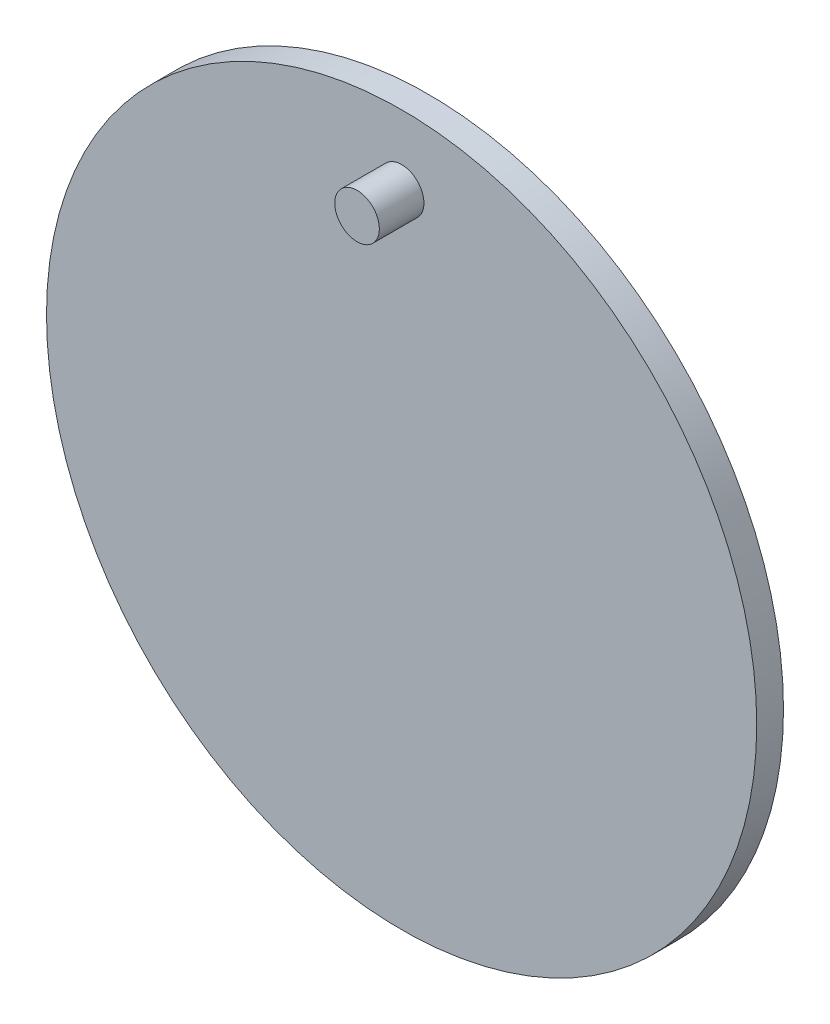
SolidWorks part; units mm, degrees
ref_plane "前视基准面" through (0, 0, 0) normal (0, 0, 1) x (1, 0, 0)
ref_plane "上视基准面" through (0, 0, 0) normal (0, 1, 0) x (1, 0, 0)
ref_plane "右视基准面" through (0, 0, 0) normal (1, 0, 0) x (0, 0, -1)
sketch "草图1" plane through (0, 0, 0) normal (0, 0, 1) x (1, 0, 0)
  circle A0 centre (0, 0) radius 39.83
extrude "凸台-拉伸1" add sketch "草图1" along normal blind 3
sketch "草图2" plane through (0, 0, 3) normal (0, 0, 1) x (1, 0, 0)
  line L0 (0, -1.65) -> (0, 1.65) construction
  circle A0 centre (0, 32) radius 2.5
  dimension "D1" = 32
  dimension "D2" = 5
extrude "凸台-拉伸2" add sketch "草图2" along normal blind 5
